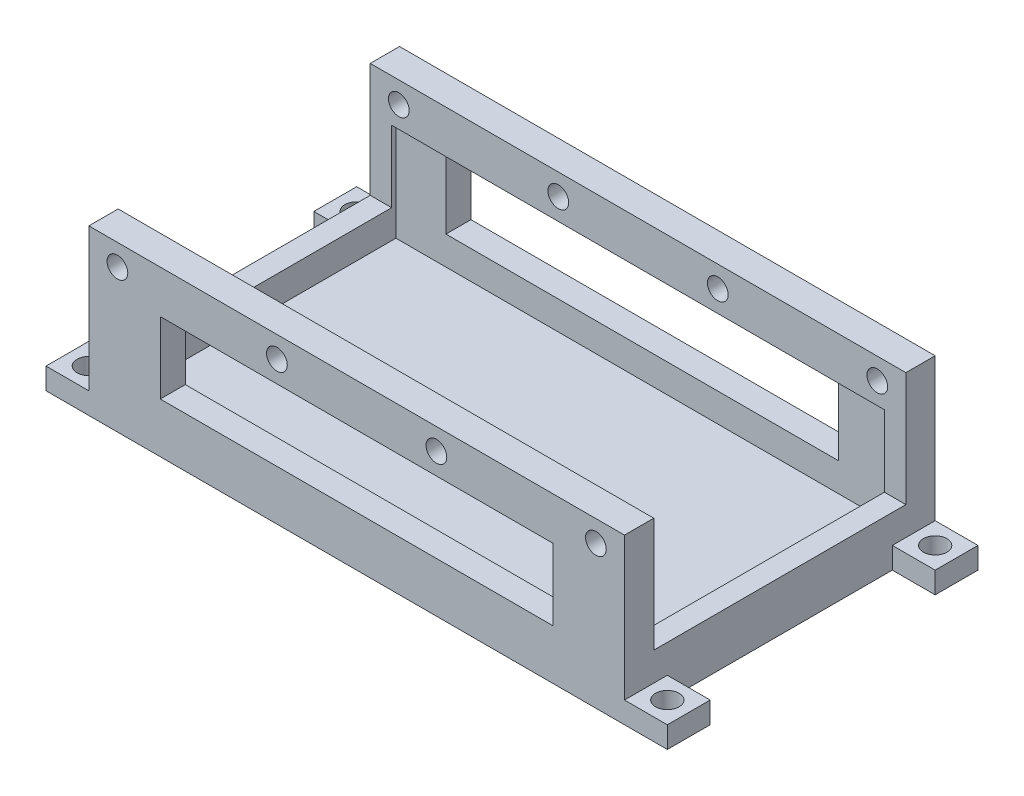
SolidWorks part; units mm, degrees
ref_plane "Front Plane" through (0, 0, 0) normal (0, 0, 1) x (1, 0, 0)
ref_plane "Top Plane" through (0, 0, 0) normal (0, 1, 0) x (1, 0, 0)
ref_plane "Right Plane" through (0, 0, 0) normal (1, 0, 0) x (0, 0, -1)
sketch "Sketch1" plane through (0, 0, 0) normal (0, 1, 0) x (1, 0, 0)
  line L0 (-34.5, -964.5) -> (-34.5, 49035.5) construction
  line L1 (0, 0) -> (-69, 0)
  line L2 (0, 0) -> (0, 35.5)
  line L3 (0, 35.5) -> (-69, 35.5)
  line L4 (-69, 0) -> (-69, 35.5)
  line L5 (-72, 39.5) -> (3, 39.5)
  line L6 (-72, 39.5) -> (-72, -4)
  line L7 (-72, -4) -> (3, -4)
  line L8 (3, 39.5) -> (3, -4)
  line L9 (-72, -4) -> (-78, -4)
  line L10 (-72, -4) -> (-72, 2)
  line L11 (-72, 2) -> (-78, 2)
  line L12 (-78, -4) -> (-78, 2)
  line L13 (-1071, 17.75) -> (48929, 17.75) construction
  line L14 (3, 2) -> (9, 2)
  line L15 (9, -4) -> (9, 2)
  line L16 (3, -4) -> (9, -4)
  line L17 (3, -4) -> (3, 2)
  line L18 (3, 39.5) -> (9, 39.5)
  line L19 (9, 39.5) -> (9, 33.5)
  line L20 (3, 33.5) -> (9, 33.5)
  line L21 (3, 39.5) -> (3, 33.5)
  line L22 (-72, 33.5) -> (-78, 33.5)
  line L23 (-78, 39.5) -> (-78, 33.5)
  line L24 (-72, 39.5) -> (-78, 39.5)
  line L25 (-72, 39.5) -> (-72, 33.5)
  circle A0 centre (-75, -1) radius 1.65
  circle A1 centre (6, -1) radius 1.65
  circle A2 centre (6, 36.5) radius 1.65
  circle A3 centre (-75, 36.5) radius 1.65
  point P15 (-75, 2)
  point P17 (-78, -1)
  point P21 (-34.5, 35.5)
  point P22 (-72, 17.75)
  dimension "D8" = 3.3
  dimension "D1" = 35.5
  dimension "D2" = 69
  dimension "D3" = 3
  dimension "D4" = 4
  dimension "D5" = 4
  dimension "D7" = 6
extrude "Boss-Extrude1" add sketch "Sketch1" along normal blind 3 contours L6 L24 L23 L22 A3 | L8 L5 L6 L7 L1 L4 L3 L2 | A0 | L8 L16 L15 L14 A1 | L8 L20 L19 L18 A2 | L9 L12 L11 L10
sketch "Sketch2" plane through (0, 3, 0) normal (0, 1, 0) x (1, 0, 0)
  line L0 (3, 33.5) -> (3, 2) construction
  line L1 (-69, 36) -> (0, 36)
  line L2 (-69, 36) -> (-69, -0.5)
  line L3 (-69, -0.5) -> (0, -0.5)
  line L4 (0, 36) -> (0, -0.5)
  line L5 (-72, 33.5) -> (-72, 2) construction
  line L6 (9, 39.5) -> (-78, 39.5) construction
  line L7 (-78, -4) -> (9, -4) construction
  line L20 (-72, 33.5) -> (-72, 39.5)
  line L21 (-72, 2) -> (-72, -4)
  line L22 (3, 2) -> (3, -4)
  line L23 (3, 33.5) -> (3, 39.5)
  line L32 (-78, 33.5) -> (-72, 33.5)
  line L33 (-72, 33.5) -> (-72, 2)
  line L34 (-72, 2) -> (-78, 2)
  line L35 (-78, 2) -> (-78, -4)
  line L36 (-78, -4) -> (9, -4)
  line L37 (9, -4) -> (9, 2)
  line L38 (9, 2) -> (3, 2)
  line L39 (3, 2) -> (3, 33.5)
  line L40 (3, 33.5) -> (9, 33.5)
  line L41 (9, 33.5) -> (9, 39.5)
  line L42 (9, 39.5) -> (-78, 39.5)
  line L43 (-78, 39.5) -> (-78, 33.5)
  line L45 (-72, 33.5) -> (-72, 2)
  line L48 (-72, -4) -> (3, -4)
  line L49 (9, -4) -> (9, 2)
  line L51 (3, 2) -> (3, 33.5)
  line L53 (9, 33.5) -> (9, 39.5)
  line L54 (3, 39.5) -> (-72, 39.5)
  line M18 (-72, 33.5) -> (-72, 2)
  line M21 (-78, -4) -> (9, -4)
  line M24 (3, 2) -> (3, 33.5)
  line M27 (9, 39.5) -> (-78, 39.5)
  dimension "D1" = 3
  dimension "D2" = 3
  dimension "D3" = 3.5
  dimension "D4" = 3.5
  dimension "D6" = 36.5
  dimension "D7" = 69
  dimension "D5" = 0
extrude "Boss-Extrude2" add sketch "Sketch2" along normal blind 4 contours L23 L20 L21 L22 L1 L4 L3 L2 M24 M27 M18 M21
sketch "Sketch3" plane through (0, 7, 0) normal (0, 1, 0) x (1, 0, 0)
  line L0 (0, 36) -> (0, -0.5) construction
  line L1 (-69, -0.5) -> (0, -0.5) construction
  line L2 (-69, 36) -> (-69, -0.5) construction
  line L3 (-69, 36) -> (0, 36) construction
  line L4 (3, -4) -> (3, 39.5)
  line L5 (3, 39.5) -> (-72, 39.5)
  line L6 (-72, 39.5) -> (-72, -4)
  line L7 (-72, -4) -> (3, -4)
  line L8 (3, -4) -> (3, 0.1)
  line L9 (3, 39.5) -> (-7, 39.5)
  line L10 (-72, 39.5) -> (-72, 35.4)
  line L11 (-72, -4) -> (-62, -4)
  line L12 (0, 36) -> (0, 35.4)
  line L13 (-69, -0.5) -> (-62, -0.5)
  line L14 (-69, 36) -> (-69, 35.4)
  line L15 (-69, 36) -> (-62, 36)
  line L16 (-69, 35.4) -> (-72, 35.4)
  line L17 (-62, 36) -> (-62, 39.5)
  line L18 (-34.5, -964.5) -> (-34.5, 49035.5) construction
  line L19 (-1071, 17.75) -> (48929, 17.75) construction
  line L20 (0, 35.4) -> (3, 35.4)
  line L21 (-7, 36) -> (-7, 39.5)
  line L22 (0, 0.1) -> (3, 0.1)
  line L23 (-7, -0.5) -> (-7, -4)
  line L24 (-62, -0.5) -> (-62, -4)
  line L25 (-69, 0.1) -> (-72, 0.1)
  line L26 (-72, 0.1) -> (-72, -4)
  line L27 (-69, 0.1) -> (-69, -0.5)
  line L28 (-7, -0.5) -> (0, -0.5)
  line L29 (-7, -4) -> (3, -4)
  line L30 (0, 0.1) -> (0, -0.5)
  line L31 (3, 35.4) -> (3, 39.5)
  line L32 (-7, 36) -> (0, 36)
  line L33 (-62, 39.5) -> (-72, 39.5)
  dimension "D2" = 10
  dimension "D3" = 4.1
  dimension "D1" = 0
extrude "Boss-Extrude3" add sketch "Sketch3" along normal blind 10
sketch "Sketch4" plane through (0, 17, 0) normal (0, 1, 0) x (1, 0, 0)
  line L1 (-72, 39.5) -> (3, 39.5)
  line L2 (-72, 39.5) -> (-72, 35.4)
  line L3 (-72, 35.4) -> (3, 35.4)
  line L4 (3, 39.5) -> (3, 35.4)
  line L5 (3, -4) -> (-72, -4)
  line L6 (3, -4) -> (3, 0.1)
  line L7 (3, 0.1) -> (-72, 0.1)
  line L8 (-72, -4) -> (-72, 0.1)
extrude "Boss-Extrude4" add sketch "Sketch4" along normal blind 6
sketch "Sketch5" plane through (0, 0, 4) normal (0, 0, 1) x (1, 0, 0)
  line L0 (-62, 17) -> (-62, 23) construction
  line L1 (-72, 23) -> (3, 23) construction
  line L2 (-72, 23) -> (-72, 3) construction
  line L3 (3, 23) -> (3, 3) construction
  circle A0 centre (-68, 20) radius 1.45
  circle A1 centre (-45.6667, 20) radius 1.45
  circle A2 centre (-23.3333, 20) radius 1.45
  circle A3 centre (-1, 20) radius 1.45
  point P8 (-62, 20)
  dimension "D1" = 2.9
  dimension "D2" = 4
  dimension "D4" = 4
  dimension "D3" = 4
extrude "Cut-Extrude1" cut sketch "Sketch5" against normal through all
